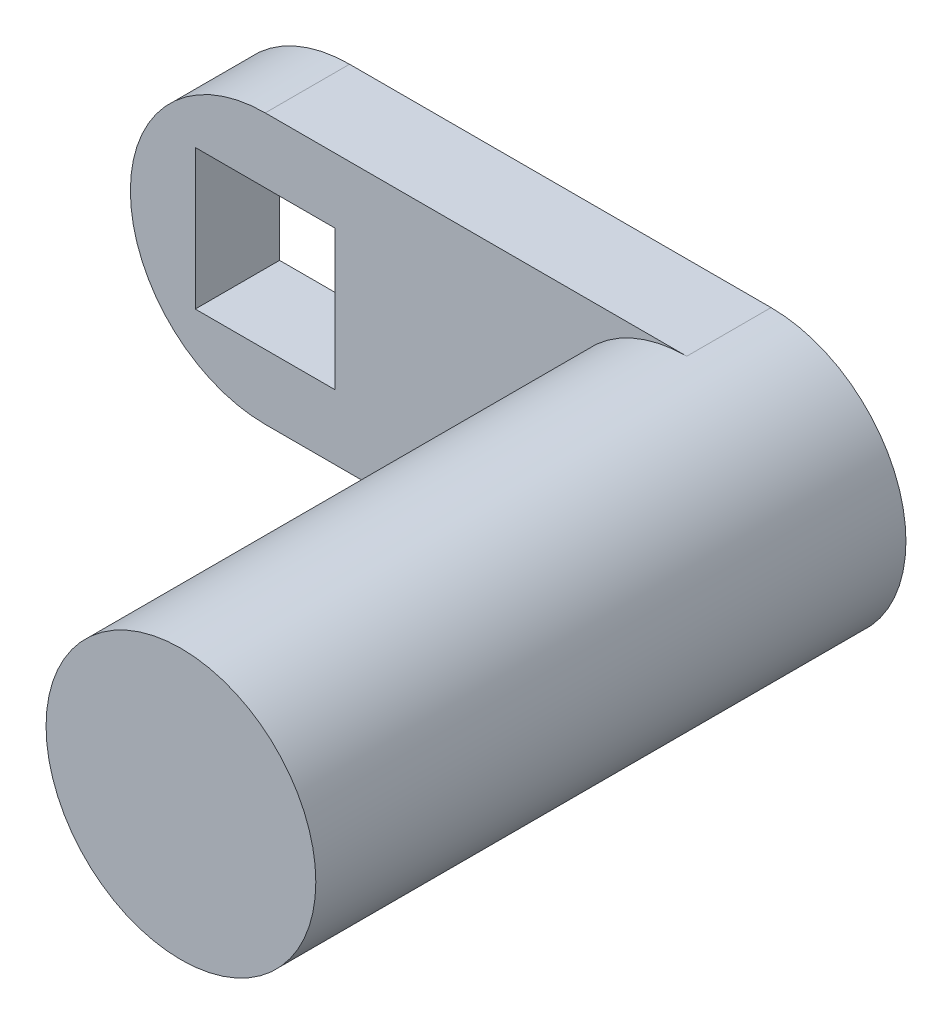
SolidWorks part; units mm, degrees
ref_plane "Front Plane" through (0, 0, 0) normal (0, 0, 1) x (1, 0, 0)
ref_plane "Top Plane" through (0, 0, 0) normal (0, 1, 0) x (1, 0, 0)
ref_plane "Right Plane" through (0, 0, 0) normal (1, 0, 0) x (0, 0, -1)
sketch "Sketch1" plane through (0, 0, 0) normal (0, 0, 1) x (1, 0, 0)
  line L0 (0, 0) -> (25, 0) construction
  line L1 (0, 8) -> (25, 8)
  line L2 (0, -8) -> (25, -8)
  line L4 (-4.15, -4.15) -> (4.15, -4.15)
  line L5 (-4.15, -4.15) -> (-4.15, 4.15)
  line L6 (-4.15, 4.15) -> (4.15, 4.15)
  line L7 (4.15, -4.15) -> (4.15, 4.15)
  line L8 (-4.15, -4.15) -> (4.15, 4.15) construction
  line L9 (-4.15, 4.15) -> (4.15, -4.15) construction
  arc A0 (0, 8) -> (0, -8) centre (0, 0) ccw
  arc A1 (25, -8) -> (25, 8) centre (25, 0) ccw
  point P3 (12.5, 0)
  point P8 (0, 0)
  dimension "D2" = 8
  dimension "D1" = 25
  dimension "D3" = 8.3
  dimension "D4" = 8.3
extrude "Boss-Extrude1" add sketch "Sketch1" along normal blind 5
sketch "Sketch2" plane through (0, 0, 5) normal (0, 0, 1) x (1, 0, 0)
  circle A0 centre (25, 0) radius 8
extrude "Boss-Extrude2" add sketch "Sketch2" along normal blind 30
